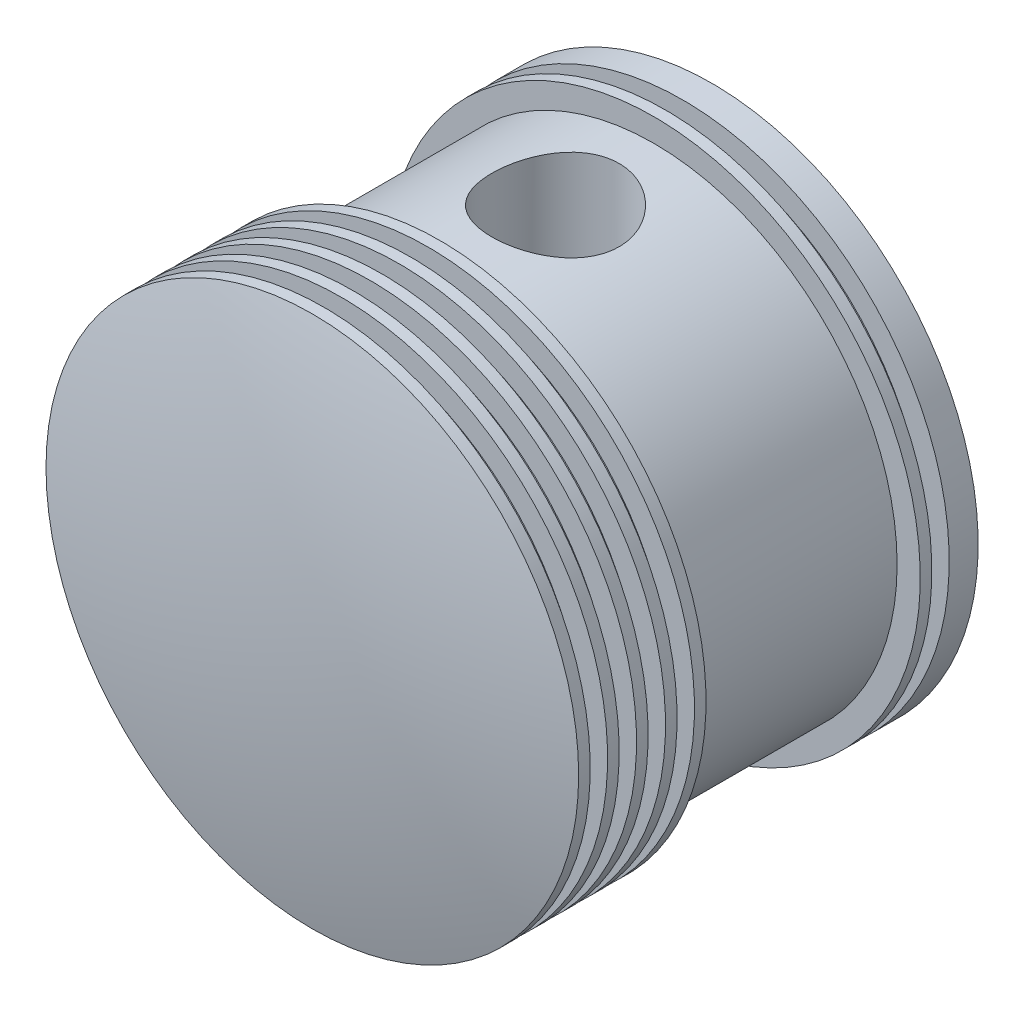
SolidWorks part; units mm, degrees
ref_plane "Front Plane" through (0, 0, 0) normal (1, 0, 0) x (0, 1, 0)
ref_plane "Top Plane" through (0, 0, 0) normal (0, 0, 1) x (0, 1, 0)
ref_plane "Right Plane" through (0, 0, 0) normal (0, 1, 0) x (-1, 0, 0)
sketch "Sketch1" plane through (0, 0, 0) normal (1, 0, 0) x (0, 1, 0)
  line L0 (-1000, 0) -> (0, 0) construction
  line L1 (0, 0) -> (0, 50000) construction
  line L2 (-46, 0) -> (0, 0)
  line L3 (-46, 0) -> (-46, 2)
  line L4 (-46, -67) -> (0, -67)
  line L5 (-42, 0) -> (-42, -3)
  line L6 (-42, -3) -> (-46, -3)
  line L7 (-46, -3) -> (-46, -5)
  line L8 (-46, -5) -> (-42, -5)
  line L9 (-42, -5) -> (-42, -8)
  line L10 (-42, -8) -> (-46, -8)
  line L11 (-46, -8) -> (-46, -10)
  line L12 (-46, -10) -> (-42, -10)
  line L13 (-42, -10) -> (-42, -13)
  line L14 (-42, -13) -> (-46, -13)
  line L15 (-46, -13) -> (-46, -15)
  line L16 (-46, -15) -> (-42, -15)
  line L17 (-42, -15) -> (-42, -18)
  line L18 (-42, -18) -> (-46, -18)
  line L19 (-46, -18) -> (-46, -20)
  line L20 (-46, -20) -> (-42, -20)
  line L21 (-42, -20) -> (-42, -57)
  line L22 (-42, -57) -> (-46, -57)
  line L23 (-46, -57) -> (-46, -59)
  line L24 (-46, -59) -> (-42, -59)
  line L25 (-42, -59) -> (-42, -62)
  line L26 (-42, -62) -> (-46, -62)
  line L27 (-46, -62) -> (-46, -67)
  line L28 (-46, 2) -> (0, 2)
  line L30 (0, 2) -> (0, -67)
  line L31 (-37, -67) -> (-37, -58)
  line L32 (-37, -58) -> (-25, -58)
  line L33 (-25, -58) -> (-25, -22)
  line L34 (-25, -22) -> (-37, -22)
  line L35 (-37, -22) -> (-37, -5)
  line L36 (-37, -5) -> (0, -5)
  line L37 (-42, -3) -> (-42, -5)
  line L38 (-42, -8) -> (-42, -10)
  line L39 (-42, -13) -> (-42, -15)
  line L40 (-42, -18) -> (-42, -20)
  line L41 (-42, -57) -> (-42, -59)
  line L42 (-42, -62) -> (-42, -67)
  line L43 (46, 0) -> (50000, 0) construction
  line L44 (0, 2) -> (0, 7.6833)
  arc A0 (-46, 2) -> (0, 7.6833) centre (0, -181.3167) cw
  dimension "D10" = 189
  dimension "D1" = 69
  dimension "D2" = 92
  dimension "D3" = 2
  dimension "D4" = 10
  dimension "D5" = 5
  dimension "D6" = 3
  dimension "D9" = 84
  dimension "D11" = 74
  dimension "D12" = 50
  dimension "D13" = 36
  dimension "D14" = 38
revolve "Revolve1" add sketch "Sketch1" angle 360 about L1
sketch "Sketch2" plane through (0, 0, 0) normal (0, 1, 0) x (-1, 0, 0)
  line L0 (0, 0) -> (0, -70.616) construction
  line L1 (-66.4973, 0) -> (63.0361, 0) construction
  line L2 (-46, -67) -> (46, -67) construction
  circle A0 centre (0, -40) radius 11
  dimension "D1" = 22
  dimension "D2" = 27
extrude "Cut-Extrude1" cut sketch "Sketch2" against normal through all both and the other way through all
